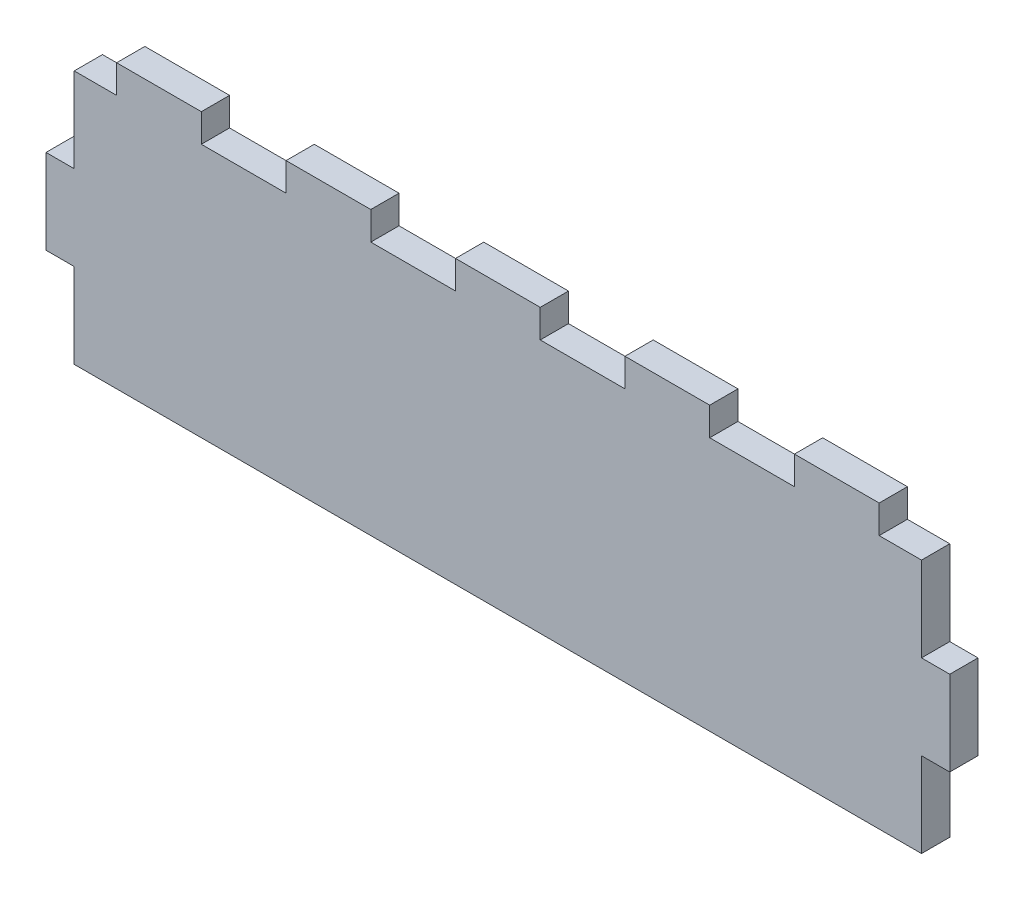
SolidWorks part; units mm, degrees
material "PINE"
ref_plane "Front Plane" through (0, 0, 0) normal (0, 0, 1) x (1, 0, 0)
ref_plane "Top Plane" through (0, 0, 0) normal (0, 1, 0) x (1, 0, 0)
ref_plane "Right Plane" through (0, 0, 0) normal (1, 0, 0) x (0, 0, -1)
sketch "Sketch1" plane through (0, 0, 0) normal (0, 0, 1) x (1, 0, 0)
  line L1 (-101.6, 31.75) -> (101.6, 31.75)
  line L2 (-101.6, 31.75) -> (-101.6, -31.75)
  line L3 (-101.6, -31.75) -> (101.6, -31.75)
  line L4 (101.6, 31.75) -> (101.6, -31.75)
  line L5 (-101.6, 31.75) -> (101.6, -31.75) construction
  line L6 (-101.6, -31.75) -> (101.6, 31.75) construction
  point P0 (0, 0)
  dimension "D1" = 63.5
  dimension "D2" = 203.2
extrude "Boss-Extrude1" add sketch "Sketch1" along normal mid plane 6.35
sketch "Sketch2" plane through (0, 0, 3.175) normal (0, 0, 1) x (1, 0, 0)
  line L1 (-101.6, 31.75) -> (-85.725, 31.75)
  line L2 (-101.6, 31.75) -> (-101.6, 25.4)
  line L3 (-101.6, 25.4) -> (-85.725, 25.4)
  line L4 (-85.725, 31.75) -> (-85.725, 25.4)
  dimension "D1" = 15.875
  dimension "D2" = 6.35
extrude "Cut-Extrude1" cut sketch "Sketch2" against normal through all
mirror "Mirror1" about plane through (0, 0, 0) normal (1, 0, 0) of "Cut-Extrude1"
sketch "Sketch3" plane through (0, 0, 3.175) normal (0, 0, 1) x (1, 0, 0)
  line L0 (85.725, 31.75) -> (-85.725, 31.75) construction
  line L1 (-66.675, 31.75) -> (-47.625, 31.75)
  line L2 (-66.675, 31.75) -> (-66.675, 25.4)
  line L3 (-66.675, 25.4) -> (-47.625, 25.4)
  line L4 (-47.625, 31.75) -> (-47.625, 25.4)
  line L5 (-85.725, 25.4) -> (-85.725, 31.75) construction
  dimension "D1" = 6.35
  dimension "D2" = 19.05
  dimension "D3" = 19.05
extrude "Cut-Extrude2" cut sketch "Sketch3" against normal through all
pattern_linear "LPattern1" count 4 spacing 38.1 along (1, 0, 0) of "Cut-Extrude2"
sketch "Sketch4" plane through (0, 0, 3.175) normal (0, 0, 1) x (1, 0, 0)
  line L1 (-101.6, 25.4) -> (-95.25, 25.4)
  line L2 (-101.6, 25.4) -> (-101.6, 6.35)
  line L3 (-101.6, 6.35) -> (-95.25, 6.35)
  line L4 (-95.25, 25.4) -> (-95.25, 6.35)
  line L5 (-101.6, -31.75) -> (-95.25, -31.75)
  line L6 (-101.6, -31.75) -> (-101.6, -12.7)
  line L7 (-101.6, -12.7) -> (-95.25, -12.7)
  line L8 (-95.25, -31.75) -> (-95.25, -12.7)
  dimension "D1" = 6.35
  dimension "D2" = 19.05
extrude "Cut-Extrude3" cut sketch "Sketch4" against normal through all
mirror "Mirror2" about plane through (0, 0, 0) normal (1, 0, 0) of "Cut-Extrude3"
